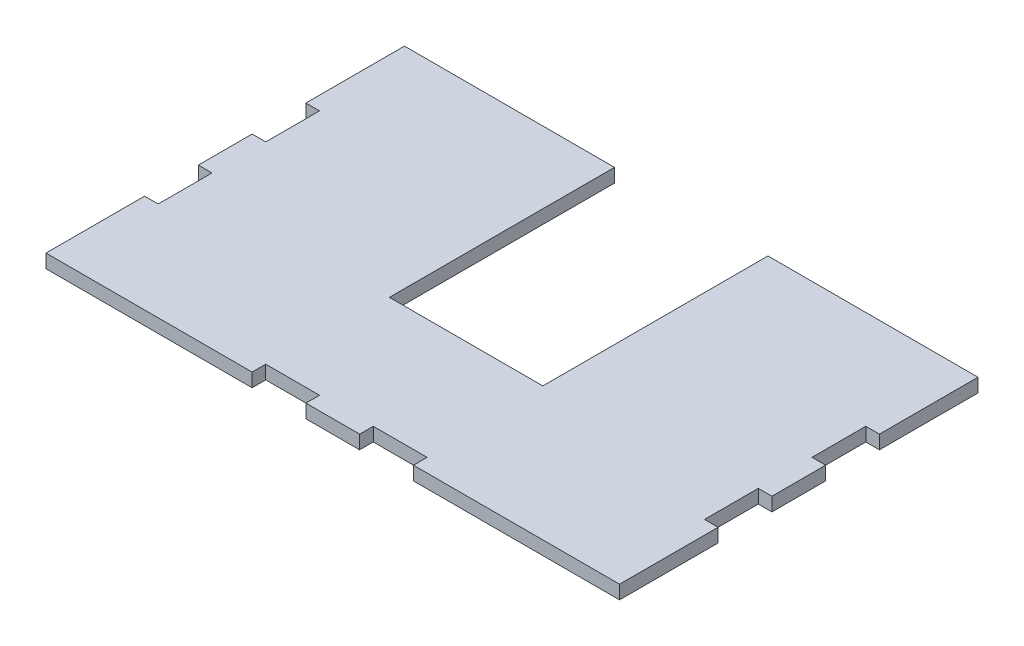
SolidWorks part; units mm, degrees
ref_plane "Front Plane" through (0, 0, 0) normal (0, 0, 1) x (1, 0, 0)
ref_plane "Top Plane" through (0, 0, 0) normal (0, 1, 0) x (1, 0, 0)
ref_plane "Right Plane" through (0, 0, 0) normal (1, 0, 0) x (0, 0, -1)
sketch "Sketch1" plane through (0, 0, 0) normal (0, 1, 0) x (1, 0, 0)
  line L1 (0, 0) -> (203.2, 0)
  line L2 (0, 0) -> (0, 177.8)
  line L3 (0, 177.8) -> (203.2, 177.8)
  line L4 (203.2, 0) -> (203.2, 177.8)
  dimension "D1" = 203.2
  dimension "D2" = 177.8
extrude "Base" add sketch "Sketch1" along normal blind 4.826
sketch "Sketch5" plane through (0, 4.826, 0) normal (0, 1, 0) x (1, 0, 0)
  line L0 (203.2, 0) -> (203.2, 177.8) construction
  line L1 (0, 177.8) -> (203.2, 177.8)
  line L2 (0, 177.8) -> (0, 127)
  line L3 (0, 127) -> (203.2, 127)
  line L4 (203.2, 177.8) -> (203.2, 127)
  dimension "D1" = 50.8
extrude "Trim" cut sketch "Sketch5" against normal through all
sketch "Sketch3" plane through (0, 4.826, 0) normal (0, 1, 0) x (1, 0, 0)
  line L1 (74.422, 127) -> (128.778, 127)
  line L2 (74.422, 127) -> (74.422, 47.244)
  line L3 (74.422, 47.244) -> (128.778, 47.244)
  line L4 (128.778, 127) -> (128.778, 47.244)
  line L6 (74.422, 104.9209) -> (0, 104.9209) construction
  line L7 (0, 127) -> (0, 0) construction
  line L8 (128.778, 104.9209) -> (203.2, 104.9209) construction
  line L9 (203.2, 0) -> (203.2, 127) construction
  line L10 (0, 127) -> (203.2, 127) construction
  line L11 (0, 0) -> (203.2, 0) construction
  point P18 (-104.8928, 161.681)
  dimension "D1" = 47.244
  dimension "D2" = 54.356
extrude "Center Cut" cut sketch "Sketch3" against normal through all
sketch "Sketch2" plane through (0, 4.826, 0) normal (0, 1, 0) x (1, 0, 0)
  line L2 (0, 127) -> (0, 0) construction
  line L3 (0, 92.075) -> (4.826, 92.075)
  line L4 (0, 92.075) -> (0, 73.025)
  line L5 (0, 0) -> (203.2, 0) construction
  line L6 (101.6, 0) -> (101.6, 50000) construction
  line L7 (0, 73.025) -> (4.826, 73.025)
  line L8 (4.826, 92.075) -> (4.826, 73.025)
  line L11 (4.826, 92.075) -> (4.826, 127) construction
  line L12 (0, 53.975) -> (4.826, 53.975)
  line L13 (0, 53.975) -> (0, 34.925)
  line L14 (0, 34.925) -> (4.826, 34.925)
  line L15 (4.826, 53.975) -> (4.826, 34.925)
  line L16 (0, 127) -> (74.422, 127) construction
  line L17 (4.826, 73.025) -> (4.826, 53.975) construction
  line L19 (4.826, 34.925) -> (4.826, 0) construction
  line L20 (198.374, 34.925) -> (198.374, 0) construction
  line L21 (198.374, 73.025) -> (198.374, 53.975) construction
  line L22 (198.374, 92.075) -> (198.374, 127) construction
  line L24 (198.374, 53.975) -> (198.374, 34.925)
  line L25 (203.2, 34.925) -> (198.374, 34.925)
  line L26 (203.2, 53.975) -> (203.2, 34.925)
  line L27 (203.2, 53.975) -> (198.374, 53.975)
  line L28 (198.374, 92.075) -> (198.374, 73.025)
  line L29 (203.2, 73.025) -> (198.374, 73.025)
  line L30 (203.2, 92.075) -> (203.2, 73.025)
  line L31 (203.2, 92.075) -> (198.374, 92.075)
  point P10 (101.6, 0)
  dimension "D1" = 19.05
  dimension "D2" = 4.826
extrude "Side Slots" cut sketch "Sketch2" against normal through all
sketch "Sketch4" plane through (0, 4.826, 0) normal (0, 1, 0) x (1, 0, 0)
  line L0 (0, 0) -> (203.2, 0) construction
  line L1 (73.025, 0) -> (92.075, 0)
  line L2 (73.025, 0) -> (73.025, 4.826)
  line L3 (73.025, 4.826) -> (92.075, 4.826)
  line L4 (92.075, 0) -> (92.075, 4.826)
  line L5 (73.025, 4.826) -> (0, 4.826) construction
  line L6 (111.125, 0) -> (130.175, 0)
  line L7 (111.125, 0) -> (111.125, 4.826)
  line L8 (111.125, 4.826) -> (130.175, 4.826)
  line L9 (130.175, 0) -> (130.175, 4.826)
  line L10 (0, 34.925) -> (0, 0) construction
  line L11 (92.075, 4.826) -> (111.125, 4.826) construction
  line L12 (130.175, 4.826) -> (203.2, 4.826) construction
  line L13 (203.2, 0) -> (203.2, 34.925) construction
  dimension "D1" = 19.05
  dimension "D2" = 4.826
  dimension "D3" = 19.05
extrude "Rear Slots" cut sketch "Sketch4" against normal through all
equation "\"material\"= \"gmaterial@Forklift_v2.assembly\""
equation "\"tab\"= \"gtab@Forklift_v2.assembly\""
equation "\"D1@Base\"=\"material\""
equation "\"D2@Sketch2\"=\"material\""
equation "\"D1@Sketch4\" = \"tab\""
equation "\"D2@Sketch4\"=\"material\""
equation "\"D1@Sketch2\"=\"tab\""
equation "\"D3@Sketch4\"=\"tab\""
